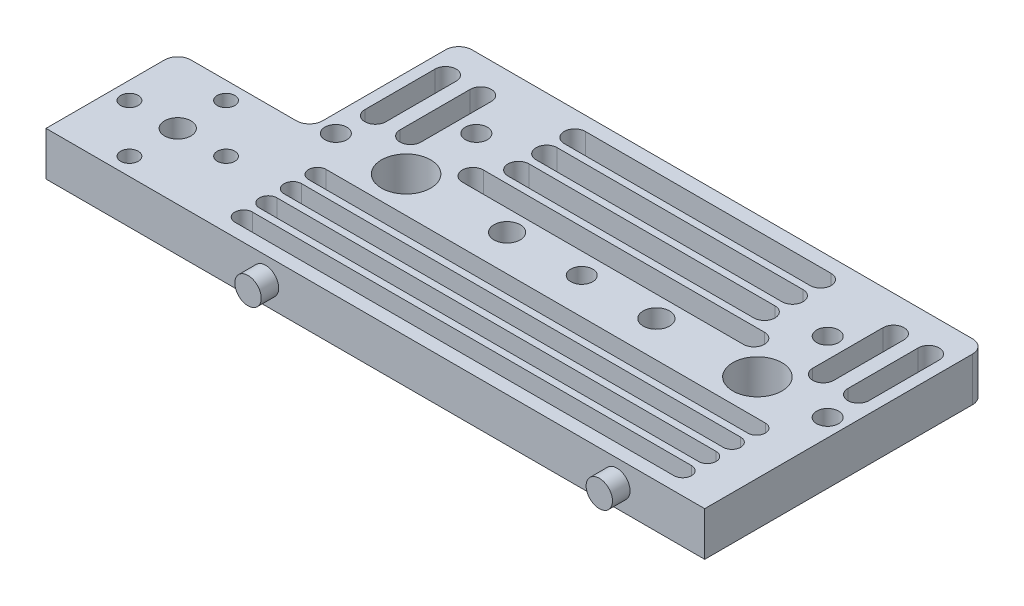
SolidWorks part; units mm, degrees
ref_plane "前视基准面" through (0, 0, 0) normal (0, 0, 1) x (1, 0, 0)
ref_plane "上视基准面" through (0, 0, 0) normal (0, 1, 0) x (1, 0, 0)
ref_plane "右视基准面" through (0, 0, 0) normal (1, 0, 0) x (0, 0, -1)
other "Configuration Table"
sketch "草图1" plane through (0, 0, 0) normal (0, 1, 0) x (1, 0, 0)
  line L0 (0, 16) -> (0, -16) construction
  line L1 (-30, 16) -> (30, 16)
  line L2 (-30, 16) -> (-30, -16)
  line L3 (-30, -16) -> (30, -16)
  line L4 (30, 16) -> (30, -16)
  line L5 (-30, 0) -> (30, 0) construction
  line L7 (-30, -16) -> (-45, -16)
  line L10 (-30, -16) -> (-30, -1)
  line L11 (-30, -1) -> (-45, -1)
  line L12 (-45, -16) -> (-45, -1)
  circle A1 centre (15.2, 0) radius 4.1
  circle A2 centre (-15.2, 0) radius 4.1
  circle A3 centre (15.2, 0) radius 2.9
  circle A4 centre (-15.2, 0) radius 2.9
  dimension "D3" = 15.2
  dimension "D4" = 8.2
  dimension "D5" = 5.8
  dimension "D1" = 60
  dimension "D2" = 32
  dimension "D6" = 15
  dimension "D7" = 15
extrude "凸台-拉伸1" add sketch "草图1" along normal blind 5 contours L2 L1 L4 L3 | L10 L7 L12 L11
sketch "草图2" plane through (0, 5, 0) normal (0, 1, 0) x (1, 0, 0)
  line L0 (0, 16) -> (0, -16) construction
  line L1 (-30, 16) -> (30, 16) construction
  line L2 (-37.5, -1) -> (-37.5, -16) construction
  line L3 (30, 16) -> (30, -16) construction
  line L4 (-30, 16) -> (-30, -16) construction
  line L5 (-45, -16) -> (30, -16) construction
  line L6 (-30, -16) -> (30, -16) construction
  line L7 (-30, -1) -> (-45, -1) construction
  line L9 (-45, -16) -> (-45, -1) construction
  line L10 (-45, -8.5) -> (-30, -8.5) construction
  circle A0 centre (8.5, 0) radius 1.5
  circle A1 centre (-8.5, 0) radius 1.5
  circle A2 centre (0, 0) radius 1.25
  circle A3 centre (20, 0) radius 4.1
  circle A4 centre (20, 0) radius 2.8
  circle A5 centre (-20, 0) radius 4.1
  circle A6 centre (-20, 0) radius 2.8
  circle A7 centre (20, 8) radius 1.25
  circle A8 centre (28, 0) radius 1.25
  circle A9 centre (-28, 0) radius 1.25
  circle A10 centre (-20, 8) radius 1.25
  circle A11 centre (-37.5, -8.5) radius 1.5
  circle A12 centre (-32, -8.5) radius 1
  circle A13 centre (-37.5, -14) radius 1
  circle A14 centre (-43, -8.5) radius 1
  circle A15 centre (-37.5, -3) radius 1
  point P12 (30, 0)
  point P36 (0, -16)
  point P48 (0, 0)
  dimension "D1" = 3
  dimension "D3" = 2.5
  dimension "D4" = 5.6
  dimension "D5" = 8.2
  dimension "D7" = 2.5
  dimension "D8" = 2.5
  dimension "D11" = 3
  dimension "D12" = 2
  dimension "D2" = 17
  dimension "D6" = 20
  dimension "D9" = 8
  dimension "D10" = 8
  dimension "D13" = 5.5
  dimension "D14" = 4
extrude "切除-拉伸1" cut sketch "草图2" along direction (0, -1, 0) on the side against the normal up to surface (5 mm away) contours A1 | A0 | A2 | A10 | A9 | A7 | A8 | A6 | A4 | A14 | A11 | A13 | A12 | A15
fillet "圆角1" radius 1.5 4 edges at (-30, 2.5, -16) (30, 2.5, -16) (-30, 2.5, 1) (-45, 2.5, 1)
sketch "草图4" plane through (0, 0, 16) normal (0, 0, 1) x (1, 0, 0)
  line L0 (30, 2.5) -> (-45, 2.5) construction
  line L1 (30, 5) -> (30, 0) construction
  line L2 (-45, 5) -> (-45, 0) construction
  line L3 (0, 0) -> (0, 5) construction
  line L4 (-45, 5) -> (30, 5) construction
  circle A0 centre (20, 2.5) radius 1.5
  circle A1 centre (-20, 2.5) radius 1.5
  dimension "D1" = 3
  dimension "D2" = 3
  dimension "D3" = 20
  dimension "D4" = 20
extrude "凸台-拉伸2" add sketch "草图4" along normal blind 2
sketch "草图5" plane through (0, 0, -16) normal (0, 0, -1) x (-1, 0, 0)
  line L0 (-28.5, 2.5) -> (28.5, 2.5) construction
  line L1 (-28.5, 5) -> (-28.5, 0) construction
  line L2 (28.5, 0) -> (28.5, 5) construction
  line L3 (0, 5) -> (0, 0) construction
  line L4 (28.5, 5) -> (-28.5, 5) construction
  line L5 (28.5, 0) -> (-28.5, 0) construction
  circle A0 centre (-20, 2.5) radius 2
  circle A2 centre (20, 2.5) radius 2
  dimension "D1" = 4
  dimension "D3" = 20
extrude "切除-拉伸2" cut sketch "草图5" against normal blind 5
sketch "草图6" plane through (0, 0, 0) normal (0, -1, 0) x (1, 0, 0)
  line L0 (0, -16) -> (0, 16) construction
  line L1 (-28.5, -16) -> (28.5, -16) construction
  line L2 (-45, 16) -> (30, 16) construction
  line L3 (-25, 13.5) -> (25, 13.5) construction
  line L4 (30, -14.5) -> (30, 16) construction
  line L5 (30, 0) -> (-30.0858, 0) construction
  line L6 (-25, 14.5) -> (25, 14.5)
  line L7 (-25, 12.5) -> (25, 12.5)
  line L8 (-25, 10.7) -> (25, 10.7) construction
  line L9 (-25, 11.7) -> (25, 11.7)
  line L10 (-25, 9.7) -> (25, 9.7)
  line L11 (-25, 7.9) -> (25, 7.9) construction
  line L12 (-25, 8.9) -> (25, 8.9)
  line L13 (-25, 6.9) -> (25, 6.9)
  line L14 (-25, 5.1) -> (25, 5.1) construction
  line L15 (-25, 6.1) -> (25, 6.1)
  line L16 (-25, 4.1) -> (25, 4.1)
  line L17 (-16, -3.6) -> (16, -3.6) construction
  line L18 (-16, -2.4) -> (16, -2.4)
  line L19 (-16, -4.8) -> (16, -4.8)
  line L20 (-14, -6.8) -> (14, -6.8) construction
  line L21 (-14, -5.6) -> (14, -5.6)
  line L22 (-14, -8) -> (14, -8)
  line L23 (-14, -10) -> (14, -10) construction
  line L24 (-14, -8.8) -> (14, -8.8)
  line L25 (-14, -11.2) -> (14, -11.2)
  line L26 (-14, -13.2) -> (14, -13.2) construction
  line L27 (-14, -12) -> (14, -12)
  line L28 (-14, -14.4) -> (14, -14.4)
  line L29 (-23.5, -4) -> (-23.5, -12) construction
  line L30 (-22.3, -4) -> (-22.3, -12)
  line L31 (-24.7, -4) -> (-24.7, -12)
  line L32 (-27.5, -4) -> (-27.5, -12) construction
  line L33 (-26.3, -4) -> (-26.3, -12)
  line L34 (-28.7, -4) -> (-28.7, -12)
  line L35 (23.5, -4) -> (23.5, -12) construction
  line L36 (22.3, -4) -> (22.3, -12)
  line L37 (24.7, -4) -> (24.7, -12)
  line L38 (27.5, -4) -> (27.5, -12) construction
  line L39 (26.3, -4) -> (26.3, -12)
  line L40 (28.7, -4) -> (28.7, -12)
  line L41 (-30, -14.5) -> (-30, -0.5) construction
  line L42 (-14, -8) -> (-30, -8) construction
  arc A0 (-30, -0.5) -> (-31.5, 1) centre (-31.5, -0.5) ccw construction
  arc A1 (-25, 14.5) -> (-25, 12.5) centre (-25, 13.5) ccw
  arc A2 (25, 12.5) -> (25, 14.5) centre (25, 13.5) ccw
  arc A3 (-25, 11.7) -> (-25, 9.7) centre (-25, 10.7) ccw
  arc A4 (25, 9.7) -> (25, 11.7) centre (25, 10.7) ccw
  arc A5 (-25, 8.9) -> (-25, 6.9) centre (-25, 7.9) ccw
  arc A6 (25, 6.9) -> (25, 8.9) centre (25, 7.9) ccw
  arc A7 (-25, 6.1) -> (-25, 4.1) centre (-25, 5.1) ccw
  arc A8 (25, 4.1) -> (25, 6.1) centre (25, 5.1) ccw
  arc A9 (-16, -2.4) -> (-16, -4.8) centre (-16, -3.6) ccw
  arc A10 (16, -4.8) -> (16, -2.4) centre (16, -3.6) ccw
  arc A11 (-14, -5.6) -> (-14, -8) centre (-14, -6.8) ccw
  arc A12 (14, -8) -> (14, -5.6) centre (14, -6.8) ccw
  arc A13 (-14, -8.8) -> (-14, -11.2) centre (-14, -10) ccw
  arc A14 (14, -11.2) -> (14, -8.8) centre (14, -10) ccw
  arc A15 (-14, -12) -> (-14, -14.4) centre (-14, -13.2) ccw
  arc A16 (14, -14.4) -> (14, -12) centre (14, -13.2) ccw
  arc A17 (-22.3, -4) -> (-24.7, -4) centre (-23.5, -4) ccw
  arc A18 (-24.7, -12) -> (-22.3, -12) centre (-23.5, -12) ccw
  arc A19 (-26.3, -4) -> (-28.7, -4) centre (-27.5, -4) ccw
  arc A20 (-28.7, -12) -> (-26.3, -12) centre (-27.5, -12) ccw
  arc A21 (22.3, -4) -> (24.7, -4) centre (23.5, -4) cw
  arc A22 (24.7, -12) -> (22.3, -12) centre (23.5, -12) cw
  arc A23 (26.3, -4) -> (28.7, -4) centre (27.5, -4) cw
  arc A24 (28.7, -12) -> (26.3, -12) centre (27.5, -12) cw
  point P17 (0, 13.5)
  point P23 (0, 10.7)
  point P30 (0, 7.9)
  point P37 (0, 5.1)
  point P44 (0, -3.6)
  point P51 (0, -6.8)
  point P58 (0, -10)
  point P65 (0, -13.2)
  point P73 (-23.5, -8)
  point P79 (-27.5, -8)
  point P87 (23.5, -8)
  point P94 (27.5, -8)
  point P103 (0, 0)
  dimension "D1" = 50
  dimension "D2" = 50
  dimension "D3" = 50
  dimension "D4" = 50
  dimension "D5" = 1
  dimension "D6" = 1
  dimension "D7" = 1
  dimension "D8" = 1
  dimension "D9" = 32
  dimension "D10" = 28
  dimension "D11" = 28
  dimension "D12" = 28
  dimension "D13" = 1.2
  dimension "D14" = 1.2
  dimension "D15" = 1.2
  dimension "D16" = 1.2
  dimension "D17" = 2.5
  dimension "D18" = 2.8
  dimension "D19" = 2.8
  dimension "D20" = 2.8
  dimension "D21" = 2.8
  dimension "D22" = 3.2
  dimension "D23" = 3.2
  dimension "D24" = 3.2
  dimension "D25" = 8
  dimension "D26" = 8
  dimension "D27" = 1.2
  dimension "D28" = 1.2
  dimension "D29" = 2.5
  dimension "D30" = 4
extrude "切除-拉伸3" cut sketch "草图6" against normal up to surface (5 mm away) up to face at (-43, 5, 9.5)
